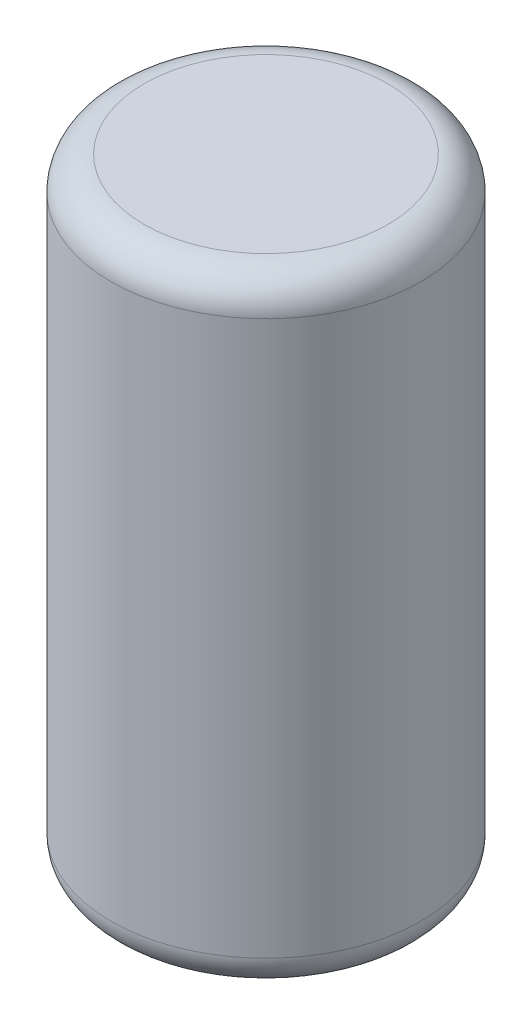
SolidWorks part; units mm, degrees
material "AISI 1015 Steel, Cold Drawn (SS)"
ref_plane "Front Plane" through (0, 0, 0) normal (0, 0, 1) x (1, 0, 0)
ref_plane "Top Plane" through (0, 0, 0) normal (0, 1, 0) x (1, 0, 0)
ref_plane "Right Plane" through (0, 0, 0) normal (1, 0, 0) x (0, 0, -1)
sketch "Sketch1" plane through (0, 0, 0) normal (0, 1, 0) x (1, 0, 0)
  circle A0 centre (0, 0) radius 1.1906
  dimension "D1" = 2.3813
extrude "Boss-Extrude1" add sketch "Sketch1" along normal blind 4.7625
fillet "Fillet2" radius 0.254 2 edges at (0, 0, 1.1906) (0, 4.7625, 1.1906)
